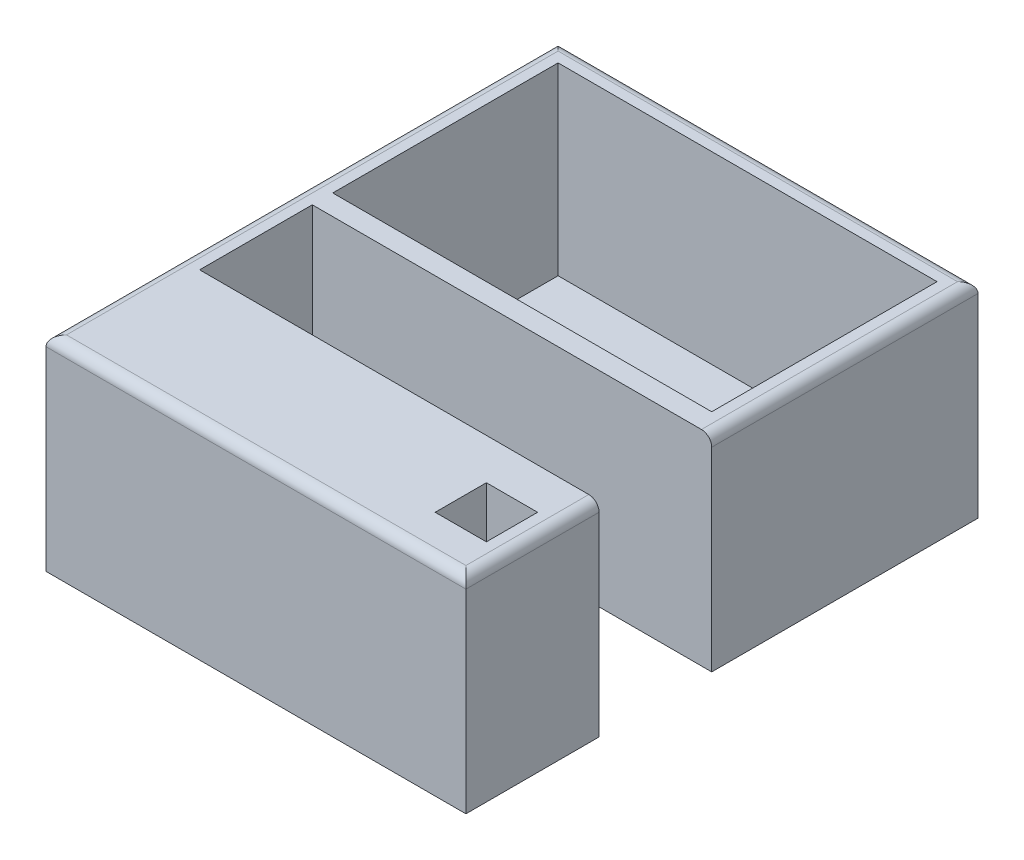
SolidWorks part; units mm, degrees
ref_plane "Front Plane" through (0, 0, 0) normal (0, 0, 1) x (1, 0, 0)
ref_plane "Top Plane" through (0, 0, 0) normal (0, 1, 0) x (1, 0, 0)
ref_plane "Right Plane" through (0, 0, 0) normal (1, 0, 0) x (0, 0, -1)
sketch "Sketch1" plane through (0, 0, 0) normal (0, 1, 0) x (1, 0, 0)
  line L0 (20.5, 25) -> (20.5, -1)
  line L1 (-20.5, 25) -> (20.5, 25)
  line L2 (-20.5, 25) -> (-20.5, -25)
  line L3 (-20.5, -25) -> (20.5, -25)
  line L4 (20.5, -12) -> (20.5, -25)
  line L5 (-20.5, 25) -> (20.5, -25) construction
  line L6 (-20.5, -25) -> (20.5, 25) construction
  line L7 (20.5, -12) -> (-17.5, -12)
  line L9 (20.5, -1) -> (-17.5, -1)
  line L10 (-17.5, -12) -> (-17.5, -1)
  point P0 (0, 0)
  dimension "D1" = 50
  dimension "D2" = 41
  dimension "D3" = 13
  dimension "D4" = 11
  dimension "D5" = 3
extrude "Boss-Extrude1" add sketch "Sketch1" along normal blind 2
sketch "Sketch2" plane through (0, 2, 0) normal (0, 1, 0) x (1, 0, 0)
  line L0 (-17.5, -1) -> (20.5, -1) construction
  line L1 (-20.5, 25) -> (20.5, 25)
  line L2 (-20.5, 25) -> (-20.5, -25)
  line L3 (-17.5, -1) -> (-18.5, -1)
  line L4 (20.5, -25) -> (-20.5, -25)
  line L5 (-18.5, 23) -> (18.5, 23)
  line L6 (-18.5, 23) -> (-18.5, 1)
  line L7 (-18.5, 1) -> (18.5, 1)
  line L8 (18.5, 23) -> (18.5, 1)
  line L9 (-18.5, -12) -> (20.5, -12)
  line L10 (13.5, -16) -> (18.5, -16)
  line L11 (13.5, -16) -> (13.5, -21)
  line L12 (13.5, -21) -> (18.5, -21)
  line L13 (18.5, -16) -> (18.5, -21)
  line L14 (20.5, -12) -> (20.5, -25)
  line L15 (-18.5, -1) -> (-18.5, -12)
  line M10 (20.5, -25) -> (20.5, -12)
  line M11 (20.5, -12) -> (-17.5, -12)
  line M13 (-17.5, -1) -> (20.5, -1)
  line M14 (20.5, -1) -> (20.5, 25)
  line M15 (20.5, 25) -> (-20.5, 25)
  line M16 (-20.5, 25) -> (-20.5, -25)
  line M17 (-20.5, -25) -> (20.5, -25)
  dimension "D1" = 2
  dimension "D3" = 2
  dimension "D4" = 2
  dimension "D5" = 4
  dimension "D8" = 9
extrude "Boss-Extrude3" add sketch "Sketch2" along normal blind 18 contours L15 L3 L9 L5 L8 L7 L6 L10 L13 L12 L11 M13 M14 M15 M16 M17 M10 M11
sketch "Sketch3" plane through (0, 2, 0) normal (0, 1, 0) x (1, 0, 0)
  line L0 (20.5, -25) -> (20.5, -12) construction
  line L1 (-20.5, -25) -> (20.5, -25) construction
  line L2 (20.5, 25) -> (-20.5, 25) construction
  line L3 (20.5, -1) -> (20.5, 25) construction
  circle A0 centre (16, 20.5) radius 1.25
  circle A1 centre (16, -18.5) radius 1.25
  dimension "D1" = 2.5
  dimension "D3" = 6.5
  dimension "D4" = 2.5
  dimension "D2" = 4.5
  dimension "D5" = 4.5
  dimension "D6" = 4.5
extrude "Cut-Extrude1" cut sketch "Sketch3" against normal through all
fillet "Fillet1" radius 1 5 edges at (20.5, 20, -12) (0, 20, -25) (-20.5, 20, 0) (0, 20, 25) (20.5, 20, 18.5)
